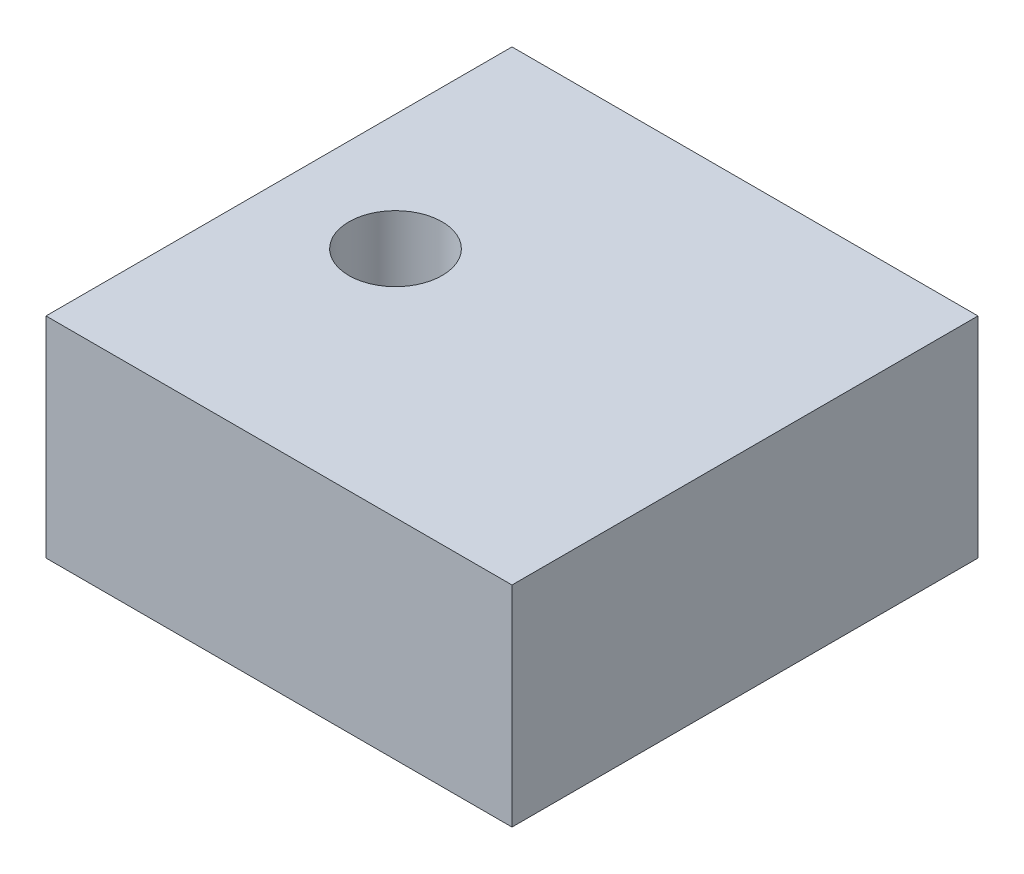
SolidWorks part; units mm, degrees
ref_plane "Front Plane" through (0, 0, 0) normal (0, 0, 1) x (1, 0, 0)
ref_plane "Top Plane" through (0, 0, 0) normal (0, 1, 0) x (1, 0, 0)
ref_plane "Right Plane" through (0, 0, 0) normal (1, 0, 0) x (0, 0, -1)
sketch "Sketch1" plane through (0, 0, 0) normal (0, 1, 0) x (1, 0, 0)
  line L0 (0, 20) -> (0, -20) construction
  line L1 (-20, -20) -> (20, -20)
  line L2 (-20, -20) -> (-20, 20)
  line L3 (-20, 20) -> (20, 20)
  line L4 (20, -20) -> (20, 20)
  line L5 (-20, -20) -> (20, 20) construction
  line L6 (-20, 20) -> (20, -20) construction
  line L7 (-20, 0) -> (20, 0) construction
  circle A2 centre (-10, 0) radius 4
  point P0 (0, 0)
  dimension "D5" = 8
  dimension "D1" = 40
  dimension "D2" = 40
  dimension "D6" = 10
extrude "Boss-Extrude1" add sketch "Sketch1" along normal blind 18
equation "\"Case_Width\" = 790mm"
equation "\"Case_Depth\" = 470mm"
equation "\"Tank_Width\" = 660mm"
equation "\"WoodSheet_Thickness\" = 18mm"
equation "\"D1@Boss-Extrude1\"=\"WoodSheet_Thickness\""
